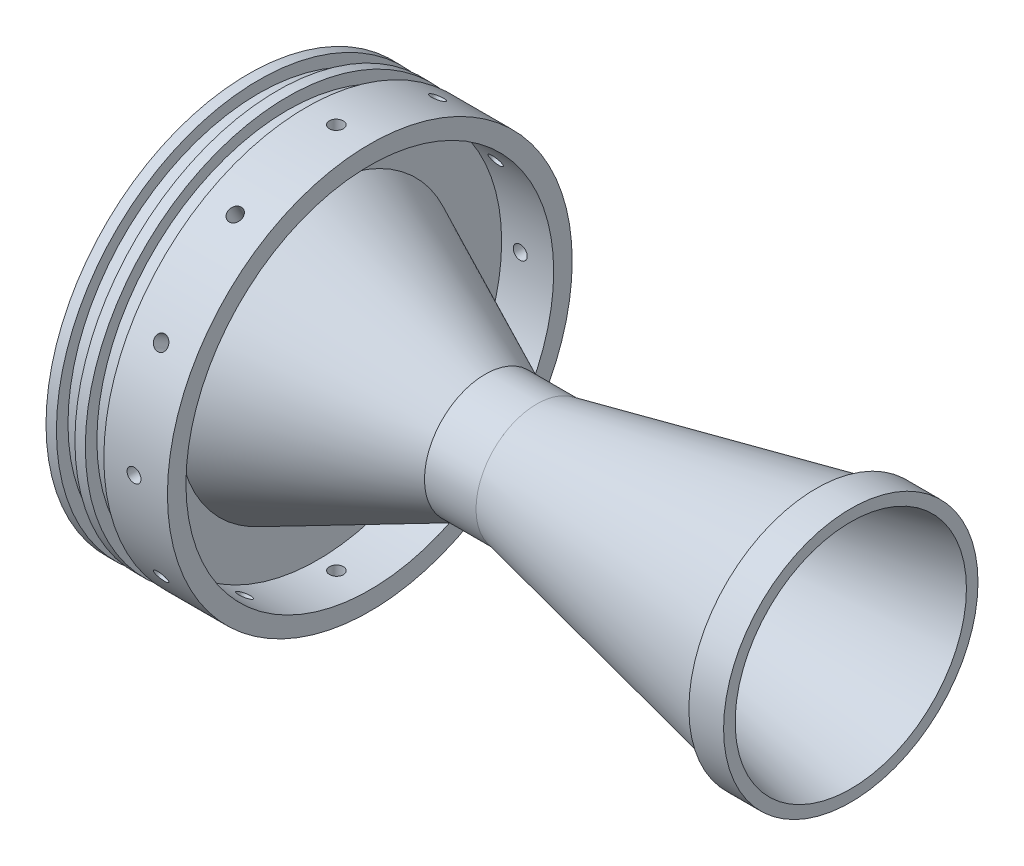
SolidWorks part; units mm, degrees
material "AISI 304"
ref_plane "Front Plane" through (0, 0, 0) normal (0, 0, 1) x (1, 0, 0)
ref_plane "Top Plane" through (0, 0, 0) normal (0, 1, 0) x (1, 0, 0)
ref_plane "Right Plane" through (0, 0, 0) normal (1, 0, 0) x (0, 0, -1)
sketch "Sketch1" plane through (0, 0, 0) normal (0, 0, 1) x (1, 0, 0)
  line L0 (0, 0) -> (0, -60)
  line L1 (0, -60) -> (18, -60)
  line L2 (18, -60) -> (18, -40)
  line L3 (18, -40) -> (50, -40)
  line L4 (50, -40) -> (50, -60)
  line L5 (50, -60) -> (68, -60)
  line L6 (68, -60) -> (68, -40)
  line L7 (68, -40) -> (100, -40)
  line L8 (100, -40) -> (100, -60)
  line L9 (100, -60) -> (210, -60)
  line L10 (210, -60) -> (210, -28)
  line L11 (210, -28) -> (120, -28)
  line L12 (120, -28) -> (120, 50)
  line L13 (0, 0) -> (75, 75)
  line L14 (75, 75) -> (396.676, 225)
  line L22 (409.5084, 185) -> (120, 50)
  line L23 (-108.9673, 290) -> (579.4064, 290) construction
  line L26 (409.5084, 185) -> (498.6666, 185)
  line L27 (498.6666, 185) -> (981.8011, 82.3066)
  line L28 (396.676, 225) -> (406.676, 225)
  line L29 (406.676, 225) -> (1041.8011, 90)
  line L30 (1041.8011, 90) -> (1041.8011, 70)
  line L31 (1041.8011, 70) -> (981.8011, 70)
  line L32 (981.8011, 70) -> (981.8011, 82.3066)
  dimension "D1" = 350
  dimension "D2" = 105
  dimension "D3" = 200
  dimension "D4" = 60
  dimension "D5" = 20
  dimension "D6" = 32
  dimension "D7" = 110
  dimension "D8" = 60
  dimension "D9" = 210
  dimension "D10" = 110
  dimension "D11" = 120
  dimension "D12" = 45
  dimension "D13" = 25
  dimension "D14" = 20
  dimension "D15" = 65
  dimension "D16" = 10
  dimension "D17" = 12
  dimension "D18" = 75
  dimension "D19" = 18
  dimension "D20" = 18
  dimension "D21" = 32
  dimension "D22" = 20
revolve "Revolve1" add sketch "Sketch1" angle 360 about L23
sketch "Sketch3" plane through (0, 0, 0) normal (0, 1, 0) x (1, 0, 0)
  circle A0 centre (152.2, 0) radius 12
  dimension "D2" = 24
  dimension "D1" = 152.2
extrude "Cut-Extrude1" cut sketch "Sketch3" against normal blind 96
pattern_circular "CirPattern1" count 12 over 360 about axis through (-108.9673, 290, 0) along (-1, 0, 0) of "Cut-Extrude1"
scale "Scale1" bodies to scale 109 scale about centroid uniform scaling yes scale factor 0.1
